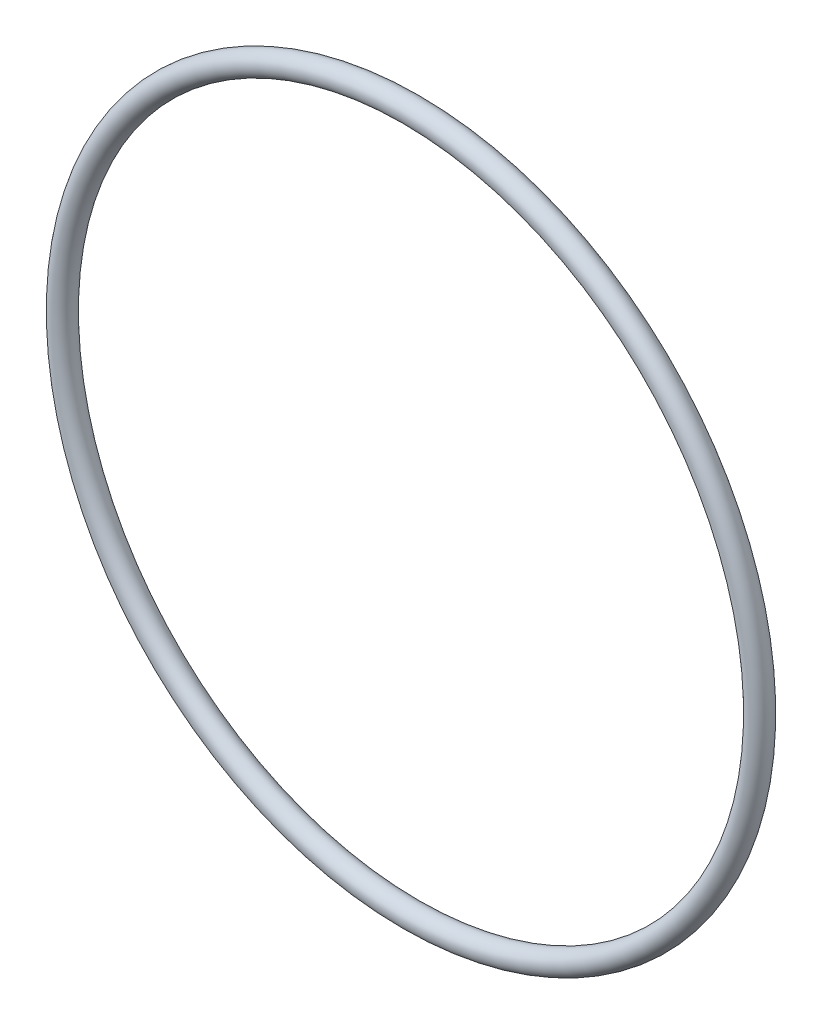
SolidWorks part; units mm, degrees
material "Rubber"
ref_plane "Front Plane" through (0, 0, 0) normal (0, 0, 1) x (1, 0, 0)
ref_plane "Top Plane" through (0, 0, 0) normal (0, 1, 0) x (1, 0, 0)
ref_plane "Right Plane" through (0, 0, 0) normal (1, 0, 0) x (0, 0, -1)
sketch "Sketch1" plane through (0, 0, 0) normal (1, 0, 0) x (0, 0, -1)
  line L0 (0, 0) -> (-25.6444, 0) construction
  circle A0 centre (0, 23) radius 0.75
  dimension "D2" = 1.5
  dimension "D1" = 23
revolve "Revolve1" add sketch "Sketch1" angle 360 about L0
